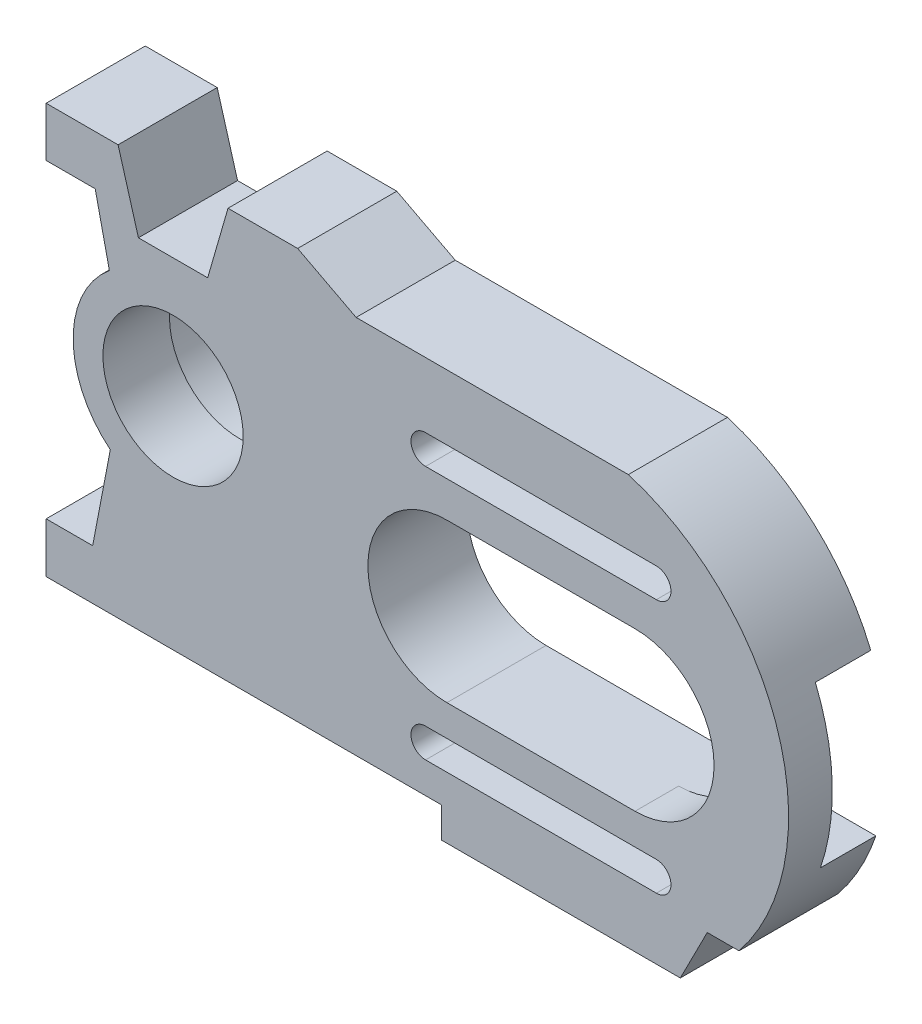
SolidWorks part; units mm, degrees
material "AISI 347 Annealed Stainless Steel (SS)"
ref_plane "Front Plane" through (0, 0, 0) normal (0, 0, 1) x (1, 0, 0)
ref_plane "Top Plane" through (0, 0, 0) normal (0, 1, 0) x (1, 0, 0)
ref_plane "Right Plane" through (0, 0, 0) normal (1, 0, 0) x (0, 0, -1)
sketch "Sketch1" plane through (0, 0, 0) normal (0, 0, 1) x (1, 0, 0)
  line L0 (0, 11.9761) -> (0, -11.7812) construction
  line L1 (-5.5943, 4.2458) -> (-7.7787, 14.0589)
  line L2 (-7.7787, 14.0589) -> (-12.6809, 14.0589)
  line L3 (-12.6809, 14.0589) -> (-12.6809, 19.0119)
  line L4 (-12.6809, 19.0119) -> (-5.4927, 19.0119)
  line L5 (-5.4927, 19.0119) -> (-3.46, 11.9761)
  line L6 (-3.46, 11.9761) -> (3.46, 11.9761)
  line L7 (3.46, 11.9761) -> (5.4927, 19.0119)
  line L8 (5.4927, 19.0119) -> (12.4523, 19.0119)
  line L9 (12.4523, 19.0119) -> (18.2944, 15.9639)
  line L10 (18.2944, 15.9639) -> (45.4978, 15.9639)
  line L11 (-5.5943, -4.2458) -> (-8.0327, -16.9545)
  line L12 (-8.0327, -16.9545) -> (-12.6809, -16.9545)
  line L13 (-12.6809, -16.9545) -> (-12.6809, -21.9583)
  line L14 (-12.6809, -21.9583) -> (26.8415, -21.9583)
  line L15 (-60.2682, 0) -> (61.0498, 0) construction
  line L16 (26.8415, -21.9583) -> (26.8415, -25.0063)
  line L17 (26.8415, -25.0063) -> (50.6921, -25.0063)
  line L18 (50.6921, -25.0063) -> (53.3845, -19.7231)
  line L19 (53.3845, -19.7231) -> (56.5594, -19.7231)
  line L20 (27.3687, -4.9403) -> (46.1647, -4.9403) construction
  line L21 (27.3687, 2.9591) -> (46.1647, 2.9591)
  line L22 (27.3687, -12.8397) -> (46.1647, -12.8397)
  line L23 (6.9883, 6.8263) -> (7.0392, -3.1254) construction
  line L24 (19.429, 2.9364) -> (19.4875, -8.5214) construction
  line L25 (19.4693, -4.9403) -> (54.0641, -4.9403) construction
  line L26 (61.5124, 9.5226) -> (61.5124, -19.1845) construction
  line L27 (25.2351, 8.001) -> (48.2983, 8.001) construction
  line L28 (25.2351, 9.4615) -> (48.2983, 9.4615)
  line L29 (25.2351, 6.5405) -> (48.2983, 6.5405)
  line L30 (25.2351, -17.399) -> (48.2983, -17.399) construction
  line L31 (25.2351, -15.9385) -> (48.2983, -15.9385)
  line L32 (25.2351, -18.8595) -> (48.2983, -18.8595)
  line L33 (23.7746, 11.8766) -> (23.7746, 2.8369) construction
  line L34 (49.7588, 11.8766) -> (49.7588, -20.7493) construction
  circle A0 centre (0, 0) radius 7.0231
  circle A1 centre (0, 0) radius 7.0104
  arc A2 (27.3687, 2.9591) -> (27.3687, -12.8397) centre (27.3687, -4.9403) ccw
  arc A3 (46.1647, -12.8397) -> (46.1647, 2.9591) centre (46.1647, -4.9403) ccw
  arc A4 (56.5594, -19.7231) -> (45.4978, 15.9639) centre (38.9593, -5.6206) ccw
  arc A5 (25.2351, 9.4615) -> (25.2351, 6.5405) centre (25.2351, 8.001) ccw
  arc A6 (48.2983, 6.5405) -> (48.2983, 9.4615) centre (48.2983, 8.001) ccw
  arc A7 (25.2351, -15.9385) -> (25.2351, -18.8595) centre (25.2351, -17.399) ccw
  arc A8 (48.2983, -18.8595) -> (48.2983, -15.9385) centre (48.2983, -17.399) ccw
  point P30 (36.7667, -4.9403)
  point P46 (36.7667, 8.001)
  point P51 (36.7667, -17.399)
  dimension "D1" = 14.0462
  dimension "D2" = 14.0208
  dimension "D10" = 11.9761
  dimension "D3" = 7.0358
  dimension "D4" = 12.6809
  dimension "D5" = 4.953
  dimension "D6" = 5.0038
  dimension "D7" = 7.1882
  dimension "D8" = 6.9596
  dimension "D9" = 40.9702
  dimension "D11" = 40.9702
  dimension "D12" = 5.842
  dimension "D13" = 7.0866
  dimension "D14" = 4.9022
  dimension "D15" = 4.6482
  dimension "D16" = 39.5224
  dimension "D17" = 3.048
  dimension "D18" = 23.8506
  dimension "D19" = 27.2034
  dimension "D20" = 20.066
  dimension "D21" = 15.7988
  dimension "D22" = 12.4206
  dimension "D23" = 34.5948
  dimension "D24" = 5.2832
  dimension "D25" = 3.175
  dimension "D26" = 7.4484
  dimension "D27" = 74.1934
  dimension "D28" = 2.6924
  dimension "D29" = 25.4
  dimension "D30" = 2.921
  dimension "D31" = 6.1468
  dimension "D32" = 25.9842
extrude "Boss-Extrude2" add sketch "Sketch1" along normal blind 9.906 contours L19 A4 L10 L9 L8 L7 L6 L5 L4 L3 L2 L1 A0 L11 L12 L13 L14 L16 L17 L18 A8 L32 A7 L31 A6 L29 A5 L28 A3 L22 A2 L21 | A0 A1
sketch "Sketch2" plane through (0, 0, 0) normal (0, 0, -1) x (-1, 0, 0)
  circle A0 centre (0, 0) radius 9.9822
  circle A1 centre (0, 0) radius 4.9848
  dimension "D1" = 19.9644
extrude "Boss-Extrude3" add sketch "Sketch2" along normal blind 1.9812
sketch "Sketch4" plane through (0, 0, 0) normal (0, 0, 1) x (1, 0, 0)
  circle A0 centre (0, 0) radius 9.9822
  circle A1 centre (0, 0) radius 7.0231
  dimension "D1" = 14.0462
extrude "Boss-Extrude4" add sketch "Sketch4" along normal up to vertex (9.906 mm away)
sketch "Sketch5" plane through (0, 0, -1.9812) normal (0, 0, -1) x (-1, 0, 0)
  circle A0 centre (0, 0) radius 8.0264
  dimension "D1" = 16.0528
extrude "Cut-Extrude1" cut sketch "Sketch5" against normal blind 5.2324
sketch "Sketch6" plane through (0, 0, 0) normal (0, 0, -1) x (-1, 0, 0)
  line L0 (-46.1647, 2.9591) -> (-59.8167, 2.9591)
  line L1 (-46.1647, -12.8397) -> (-60.3259, -12.8397)
  line L2 (-46.1647, -12.8397) -> (-46.1647, 2.9591)
  arc A0 (-45.4978, 15.9639) -> (-56.5594, -19.7231) centre (-38.9593, -5.6206) ccw construction
  arc A1 (-60.3259, -12.8397) -> (-59.8167, 2.9591) centre (-38.9593, -5.6206) cw
extrude "Cut-Extrude2" cut sketch "Sketch6" against normal blind 5.5372
sketch "Sketch7" plane through (0, -21.9583, 0) normal (0, -1, 0) x (1, 0, 0)
  line L0 (-8.9344, 9.906) -> (-8.9344, 0) construction
  line L1 (-12.6809, 9.906) -> (26.8415, 9.906) construction
  line L2 (-12.6809, 0) -> (26.8415, 0) construction
  line L3 (17.4308, 9.906) -> (17.4308, 0) construction
  line L4 (-12.6809, 9.906) -> (-12.6809, 0) construction
  circle A0 centre (-8.9344, 4.953) radius 1.9685
  circle A1 centre (17.4308, 4.953) radius 1.9685
  dimension "D1" = 3.937
  dimension "D2" = 3.7465
  dimension "D3" = 26.3652
extrude "Cut-Extrude3" cut sketch "Sketch7" against normal blind 12.7
sketch "Sketch8" plane through (0, 0, 0) normal (0, 0, -1) x (-1, 0, 0)
  line L0 (-48.2983, 8.001) -> (-25.2351, 8.001) construction
  line L1 (-48.2983, 11.303) -> (-25.2351, 11.303)
  line L2 (-48.2983, 4.699) -> (-25.2351, 4.699)
  line L3 (-48.2983, -17.399) -> (-25.2351, -17.399) construction
  line L4 (-48.2983, -14.097) -> (-25.2351, -14.097)
  line L5 (-48.2983, -20.701) -> (-25.2351, -20.701)
  arc A0 (-48.2983, 11.303) -> (-48.2983, 4.699) centre (-48.2983, 8.001) ccw
  arc A1 (-25.2351, 4.699) -> (-25.2351, 11.303) centre (-25.2351, 8.001) ccw
  arc A2 (-48.2983, -14.097) -> (-48.2983, -20.701) centre (-48.2983, -17.399) ccw
  arc A3 (-25.2351, -20.701) -> (-25.2351, -14.097) centre (-25.2351, -17.399) ccw
  point P4 (-36.7667, 8.001)
  point P9 (-36.7667, -17.399)
  dimension "D1" = 6.604
  dimension "D2" = 6.604
extrude "Cut-Extrude4" cut sketch "Sketch8" against normal blind 4.064
sketch "Sketch9" plane through (0, 0, 0) normal (0, 0, -1) x (-1, 0, 0)
  line L0 (-46.1647, -4.9403) -> (-27.3687, -4.9403) construction
